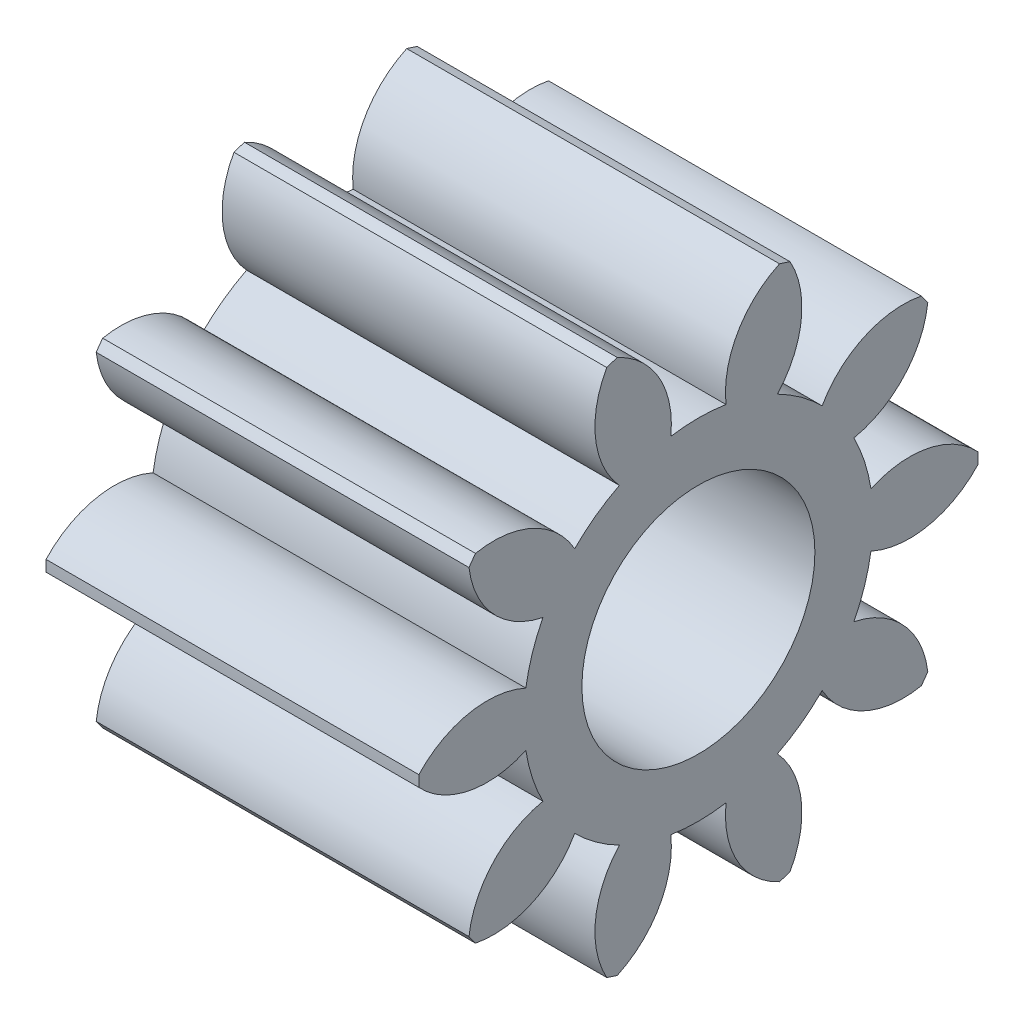
SolidWorks part; units mm, degrees
ref_plane "Plane1" through (0, 0, 0) normal (0, 0, 1) x (1, 0, 0)
ref_plane "Plane2" through (0, 0, 0) normal (0, 1, 0) x (1, 0, 0)
ref_plane "Plane3" through (0, 0, 0) normal (1, 0, 0) x (0, 0, -1)
sketch "HoldingSke" plane through (0, 0, 0) normal (0, 1, 0) x (1, 0, 0)
  line L0 (0, 0) -> (1.9696, -0.3473)
  line L1 (-15, 0) -> (100, 0) construction
  line L2 (0, 0) -> (-2.1039, 2.3779)
  line L3 (0, 0) -> (-11.863, 4.5341)
  line L4 (0, 0) -> (8.5048, 1.4996)
  line L5 (0, 0) -> (-46.8476, -17.4728)
  line L6 (0, 0) -> (-3.3159, -2.2372)
  line L7 (-2.1039, 2.3779) -> (8.6586, 51.2059)
  line L8 (-76.2, 54.61) -> (-75.9, 54.61)
  line L9 (-71.009, 38.7566) -> (-53.1078, 45.2721)
  line L10 (-76.2, 71.12) -> (104.1128, 71.12)
  line L11 (0, 0) -> (-4, 0)
  line L12 (-76.2, 101.6) -> (-76.181, 101.6)
  line L13 (24.9733, 27.94) -> (52.9518, 28.4284)
  line L14 (24.9733, 27.94) -> (24.9743, 27.94)
  line L15 (24.9733, 27.94) -> (100.4006, 29.5858)
  line L16 (-63.627, -0.5) -> (-12.827, -0.5)
  circle A0 centre (0, 0) radius 1
  circle A1 centre (0, 0) radius 1.874
  circle A2 centre (0, 0) radius 37.5
  circle A3 centre (0, 0) radius 1
  dimension "MHD" = 3.748
  dimension "Hub_dia" = 75
  dimension "Bore" = 2
  dimension "MBD" = 2
  dimension "Num_teeth" = 10
  dimension "Pitch" = 2
  dimension "Overall_len" = 50
  dimension "Show_teeth" = 10
  dimension "Thickness" = 4
  dimension "OAL" = 50.0001
  dimension "T_dim" = 0.3
  dimension "Ap" = 20
  dimension "H" = 19.05
  dimension "Pitch_radius" = 180.3128
  dimension "Width" = 4
  dimension "Backlash" = 0.019
  dimension "Addendum_fac" = 1
  dimension "Dedendum_fac" = 1.25
  dimension "Clearance_fac" = 0.25
  dimension "Dedendum_add" = 0.001
  dimension "Module" = 0.5
sketch "BasProSke" plane through (0, 0, 0) normal (0, 1, 0) x (1, 0, 0)
  line L0 (-10, 0) -> (60, 0) construction
  line L1 (0, 0) -> (0, 3)
  line L2 (0, 0) -> (4, 0)
  line L3 (4, 0) -> (4, 3)
  line L4 (4, 3) -> (0, 3)
  dimension "Thickness" = 4
  dimension "Diameter" = 6
revolve "Base-Revolve" add sketch "BasProSke" angle 360 about L0
sketch "TooCutSke" plane through (0, 0, 0) normal (1, 0, 0) x (0, 0, -1)
  line L1 (0, 0) -> (0, 107) construction
  line L2 (0, 0) -> (-0.4243, 2.4637) construction
  line L3 (0, 0) -> (-1.5292, 4.7063) construction
  line L4 (-0.4243, 2.4637) -> (-0.7646, 2.3532) construction
  arc A0 (0.2964, 1.8504) -> (-0.2964, 1.8504) centre (0, 0) ccw
  arc A1 (0.9059, 2.8866) -> (-0.9059, 2.8866) centre (0, 0) ccw
  circle A2 centre (0, 0) radius 2.5 construction
  circle A3 centre (0, 0) radius 2.3492 construction
  arc A4 (-0.2964, 1.8504) -> (-0.9059, 2.8866) centre (-1.2901, 1.9633) ccw
  arc A5 (0.9059, 2.8866) -> (0.2964, 1.8504) centre (1.2901, 1.9633) ccw
  dimension "Root_dia" = 3.748
  dimension "Overcut_dia" = 6.0508
  dimension "Pitch_dia" = 5
  dimension "Base_dia" = 4.6985
  dimension "Flank_rad" = 1
  dimension "Half_ang" = 18
  dimension "Half_CT" = 0.3578
extrude "ToothCut" cut sketch "TooCutSke" along normal through all
fillet "Breaks" [suppressed] radius 0.01
fillet "RootFillets" [suppressed] radius 0.126
pattern_circular "TeethCuts" count 10 every 36 about axis through (-10, 0, 0) along (1, 0, 0) of "ToothCut", "RootFillets", "Breaks"
sketch "HubNeaOneSke" plane through (0, 0, 0) normal (-1, 0, 0) x (0, 0, 1)
  circle A0 centre (0, 0) radius 1.874
  dimension "Diameter" = 3.748
extrude "HubNearOne" [suppressed] add sketch "HubNeaOneSke" along normal blind 46.0001
sketch "HubNeaBotSke" plane through (0, 0, 0) normal (-1, 0, 0) x (0, 0, 1)
  circle A0 centre (0, 0) radius 1.874
  dimension "Diameter" = 3.748
extrude "HubNearBoth" [suppressed] add sketch "HubNeaBotSke" along normal blind 23
ref_plane "FarPln" through (4, 0, 0) normal (1, 0, 0) x (0, 0, -1)
sketch "HubFarSke" plane through (4, 0, 0) normal (1, 0, 0) x (0, 0, -1)
  circle A0 centre (0, 0) radius 1.874
  dimension "Diameter" = 3.748
extrude "HubFar" [suppressed] add sketch "HubFarSke" along normal blind 23
sketch "BorSke" plane through (0, 0, 0) normal (1, 0, 0) x (0, 0, -1)
  circle A0 centre (0, 0) radius 1.25
  dimension "Diameter" = 2.5
extrude "Bore" cut sketch "BorSke" along normal mid plane 100.0001
sketch "KeySke" plane through (0, 0, 0) normal (1, 0, 0) x (0, 0, -1)
  line L0 (-0.4, 0) -> (-0.4, 1.3)
  line L1 (-0.4, 1.3) -> (0.4, 1.3)
  line L2 (0.4, 1.3) -> (0.4, 0)
  line L3 (0, 0) -> (0, 34) construction
  line L4 (-0.4, 0) -> (0.4, 0)
  dimension "Offset" = 1.3
  dimension "Width" = 0.8
extrude "Keyway" [suppressed] cut sketch "KeySke" along normal mid plane 100.0001
pattern_circular "Keyway2" [suppressed] count 2 every 90 about axis through (-10, 0, 0) along (1, 0, 0)
equation "' \"Module@HoldingSke\" = 6.35"
equation "' \"Num_teeth@HoldingSke\" = 12"
equation "' \"Ap@HoldingSke\" =  20"
equation "' \"Ap@HoldingSke\" = 20"
equation "' \"Width@HoldingSke\" = 0.5 * 25.4"
equation "' \"Hub_dia@HoldingSke\"= 1 * 25.4"
equation "' \"Hub_dia@HoldingSke\" = 1 * 25.4"
equation "' \"Overall_len@HoldingSke\" = 1.0 * 25.4"
equation "' \"Bore@HoldingSke\" = 0.75 * 25.4"
equation "' \"T_dim@HoldingSke\" = 0.1 * 25.4"
equation "' \"Width@KeySke\" = 0.25 * 25.4"
equation "' \"Show_teeth@HoldingSke\" = 13"
equation "' \"Backlash@HoldingSke\" = 0.009 * 25.4"
equation "' \"Addendum_fac@HoldingSke\" = 1.0"
equation "' \"Dedendum_fac@HoldingSke\" = 1.25"
equation "' \"Dedendum_add@HoldingSke\" = 0.00005 * 25.4"
equation "' \"Clearance_fac@HoldingSke\" = 0.25"
equation "\"Pitch@HoldingSke\" = 1 / \"Module@HoldingSke\""
equation "\"Overcut_dia@TooCutSke\" = (\"Num_teeth@HoldingSke\" + 2 * \"Addendum_fac@HoldingSke\") / \"Pitch@HoldingSke\" + 0.002 * 25.4"
equation "\"Pitch_dia@TooCutSke\" = \"Num_teeth@HoldingSke\" / \"Pitch@HoldingSke\""
equation "\"Base_dia@TooCutSke\" = \"Num_teeth@HoldingSke\" / \"Pitch@HoldingSke\" * cos((\"Ap@HoldingSke\"  * 3.14159265 / 180))"
equation "\"Root_dia@TooCutSke\" = (\"Num_teeth@HoldingSke\" + 2) / \"Pitch@HoldingSke\" - 2 * (\"Addendum_fac@HoldingSke\" + \"Dedendum_fac@HoldingSke\") / \"Pitch@HoldingSke\" - \"Dedendum_add@HoldingSke\" * 2"
equation "\"Half_ang@TooCutSke\" = 180 / \"Num_teeth@HoldingSke\""
equation "\"Half_CT@TooCutSke\" = \"Num_teeth@HoldingSke\" / \"Pitch@HoldingSke\" * sin((3.14159265 / 2 / \"Num_teeth@HoldingSke\")) / 2 - 7 * \"Backlash@HoldingSke\" / 4"
equation "\"Flank_rad@TooCutSke\" = \"Num_teeth@HoldingSke\" / \"Pitch@HoldingSke\" / 5"
equation "\"Radius@RootFillets\" = \"Clearance_fac@HoldingSke\" / \"Pitch@HoldingSke\" + \"Dedendum_add@HoldingSke\""
equation "\"Break_rad@Breaks\" = 0.02 / \"Pitch@HoldingSke\""
equation "\"Thickness@HoldingSke\" = \"Width@HoldingSke\""
equation "\"OAL@HoldingSke\" = \"Thickness@HoldingSke\""
equation "\"MHD@HoldingSke\" = (\"Num_teeth@HoldingSke\" + 2) / \"Pitch@HoldingSke\" - 2 * (\"Addendum_fac@HoldingSke\" + \"Dedendum_fac@HoldingSke\")  / \"Pitch@HoldingSke\" - \"Dedendum_add@HoldingSke\" * 2"
equation "\"MBD@HoldingSke\" = (\"Num_teeth@HoldingSke\" + 2) / \"Pitch@HoldingSke\" - 2 * (\"Addendum_fac@HoldingSke\" + \"Dedendum_fac@HoldingSke\")  / \"Pitch@HoldingSke\" - \"Dedendum_add@HoldingSke\" * 2 - 0.002 * 25.4"
equation "\"MHD@HoldingSke\" = ((sgn( \"MHD@HoldingSke\" - \"Hub_dia@HoldingSke\" )-1)*( \"MHD@HoldingSke\" - \"Hub_dia@HoldingSke\" ))/-2+ \"Hub_dia@HoldingSke\""
equation "\"MBD@HoldingSke\" = ((sgn( \"MBD@HoldingSke\" - \"Bore@HoldingSke\" )-1)*( \"MBD@HoldingSke\" - \"Bore@HoldingSke\" ))/-2+ \"Bore@HoldingSke\""
equation "\"OAL@HoldingSke\" = ((sgn( \"OAL@HoldingSke\" - \"Overall_len@HoldingSke\" )+1)*( \"OAL@HoldingSke\" - \"Overall_len@HoldingSke\" ))/2 + \"Overall_len@HoldingSke\" + 0.000002 * 25.4"
equation "\"Num_teeth@TeethCuts\" = int( \"Show_teeth@HoldingSke\" ) + 1"
equation "\"Num_teeth@TeethCuts\" = ((sgn( \"Num_teeth@TeethCuts\" - \"Num_teeth@HoldingSke\" )-1)*( \"Num_teeth@TeethCuts\" - \"Num_teeth@HoldingSke\" ))/-2+ \"Num_teeth@HoldingSke\""
equation "\"Num_teeth@TeethCuts\" = ((sgn( \"Num_teeth@TeethCuts\" - 2.0)+1)*( \"Num_teeth@TeethCuts\" - 2.0))/2 +2.0"
equation "\"Angle@TeethCuts\" = 360.0 / \"Num_teeth@HoldingSke\""
equation "\"Diameter@BasProSke\" = (\"Num_teeth@HoldingSke\" + 2 * \"Addendum_fac@HoldingSke\") / \"Pitch@HoldingSke\""
equation "\"Thickness@BasProSke\"  = \"Thickness@HoldingSke\""
equation "' \"Fillet_rad@BasProSke\" =  \"Thickness@HoldingSke\" * 0.05"
equation "' \"Fillet_rad@BasProSke\" = \"Thickness@HoldingSke\" * 0.05"
equation "\"MHD@HoldingSke\" = ((sgn( \"MHD@HoldingSke\" - \"Root_dia@TooCutSke\" )-1)*( \"MHD@HoldingSke\" - \"Root_dia@TooCutSke\" ))/-2+ \"Root_dia@TooCutSke\""
equation "\"Diameter@HubNeaOneSke\" = \"MHD@HoldingSke\""
equation "\"Length@HubNearOne\" = \"OAL@HoldingSke\" - \"Thickness@BasProSke\""
equation "\"Diameter@HubNeaBotSke\" = \"MHD@HoldingSke\""
equation "\"Length@HubNearBoth\" = ( \"OAL@HoldingSke\" - \"Thickness@BasProSke\" ) / 2.0"
equation "\"Thickness@FarPln\" = \"Thickness@BasProSke\""
equation "\"Diameter@HubFarSke\" = \"MHD@HoldingSke\""
equation "\"Length@HubFar\" = ( \"OAL@HoldingSke\" - \"Thickness@BasProSke\" ) / 2.0"
equation "\"Diameter@BorSke\"=\"MBD@HoldingSke\"+0.5"
equation "\"D1@Bore\" = \"OAL@HoldingSke\" * 2.0"
equation "\"D1@Keyway\" = \"OAL@HoldingSke\" * 2.0"
equation "\"Offset@KeySke\" = \"T_dim@HoldingSke\" + \"MBD@HoldingSke\" / 2.0"
